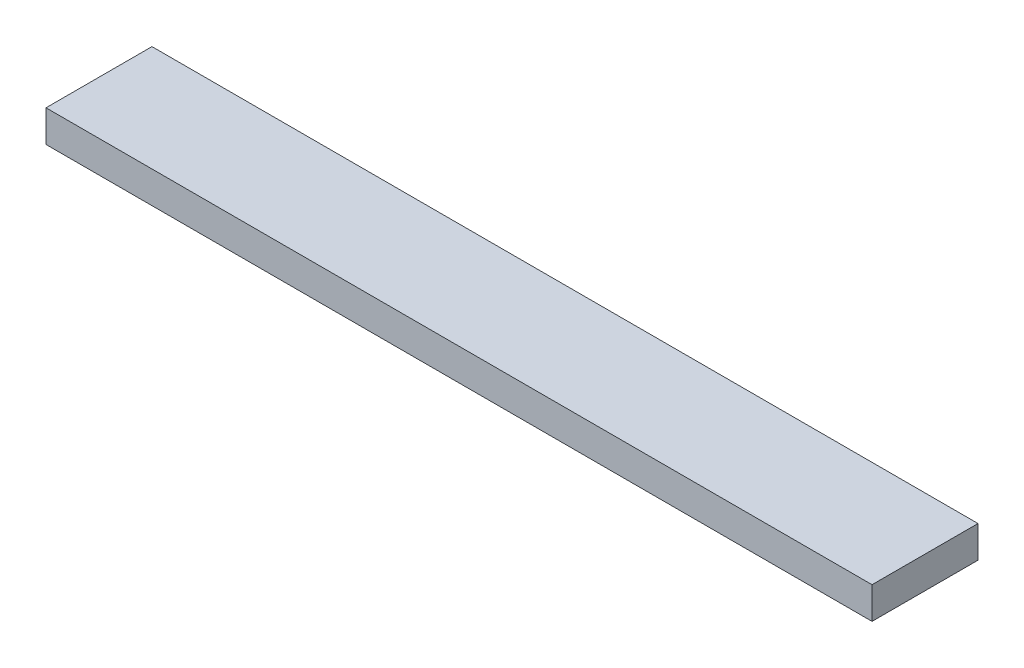
SolidWorks part; units mm, degrees
ref_plane "Front Plane" through (0, 0, 0) normal (0, 0, 1) x (1, 0, 0)
ref_plane "Top Plane" through (0, 0, 0) normal (0, 1, 0) x (1, 0, 0)
ref_plane "Right Plane" through (0, 0, 0) normal (1, 0, 0) x (0, 0, -1)
sketch "Sketch1" plane through (0, 0, 0) normal (0, 1, 0) x (1, 0, 0)
  line L1 (0, 0) -> (77.95, 0)
  line L2 (0, 0) -> (0, 10)
  line L3 (0, 10) -> (77.95, 10)
  line L4 (77.95, 0) -> (77.95, 10)
  dimension "D1" = 10
  dimension "D2" = 77.95
extrude "Boss-Extrude1" add sketch "Sketch1" along normal blind 3
